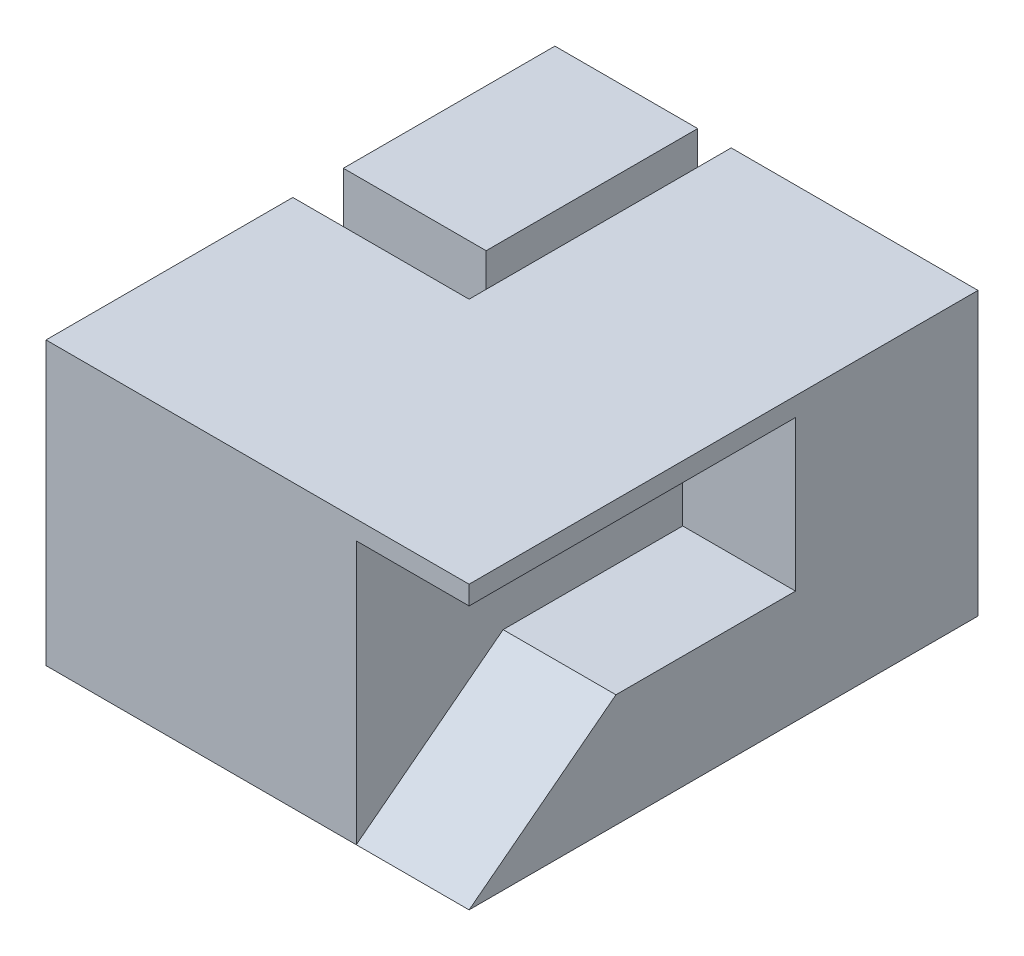
SolidWorks part; units mm, degrees
ref_plane "前视基准面" through (0, 0, 0) normal (0, 0, 1) x (1, 0, 0)
ref_plane "上视基准面" through (0, 0, 0) normal (0, 1, 0) x (1, 0, 0)
ref_plane "右视基准面" through (0, 0, 0) normal (1, 0, 0) x (0, 0, -1)
sketch "草图1" plane through (0, 0, 0) normal (0, 1, 0) x (1, 0, 0)
  line L0 (-53.866, 14.1755) -> (-53.866, -20.8245)
  line L1 (-53.866, -20.8245) -> (6.134, -20.8245)
  line L2 (6.134, -20.8245) -> (6.134, 51.3447)
  line L3 (6.134, 51.3447) -> (-28.866, 51.3447)
  line L4 (-28.866, 51.3447) -> (-28.866, 14.1755)
  line L5 (-28.866, 14.1755) -> (-53.866, 14.1755)
  line L7 (-53.866, 51.3447) -> (-33.6145, 51.3447)
  line L8 (-53.866, 51.3447) -> (-53.866, 21.3447)
  line L9 (-53.866, 21.3447) -> (-33.6145, 21.3447)
  line L10 (-33.6145, 51.3447) -> (-33.6145, 21.3447)
  dimension "D1" = 60
  dimension "D2" = 35
  dimension "D3" = 35
  dimension "D4" = 30
extrude "凸台-拉伸1" add sketch "草图1" along normal blind 40
sketch "草图2" plane through (6.134, 0, 0) normal (1, 0, 0) x (0, 0, -1)
  line L0 (-20.8245, 40) -> (-20.8245, 0) construction
  line L1 (-20.8245, 37.3269) -> (25.4654, 37.3269)
  line L2 (-20.8245, 37.3269) -> (-20.8245, 0)
  line L3 (0, 16.007) -> (25.4654, 16.007)
  line L4 (25.4654, 37.3269) -> (25.4654, 16.007)
  line L5 (-20.8245, 0) -> (0, 16.007)
  point P9 (0, 0)
extrude "切除-拉伸1" cut sketch "草图2" against normal blind 16
